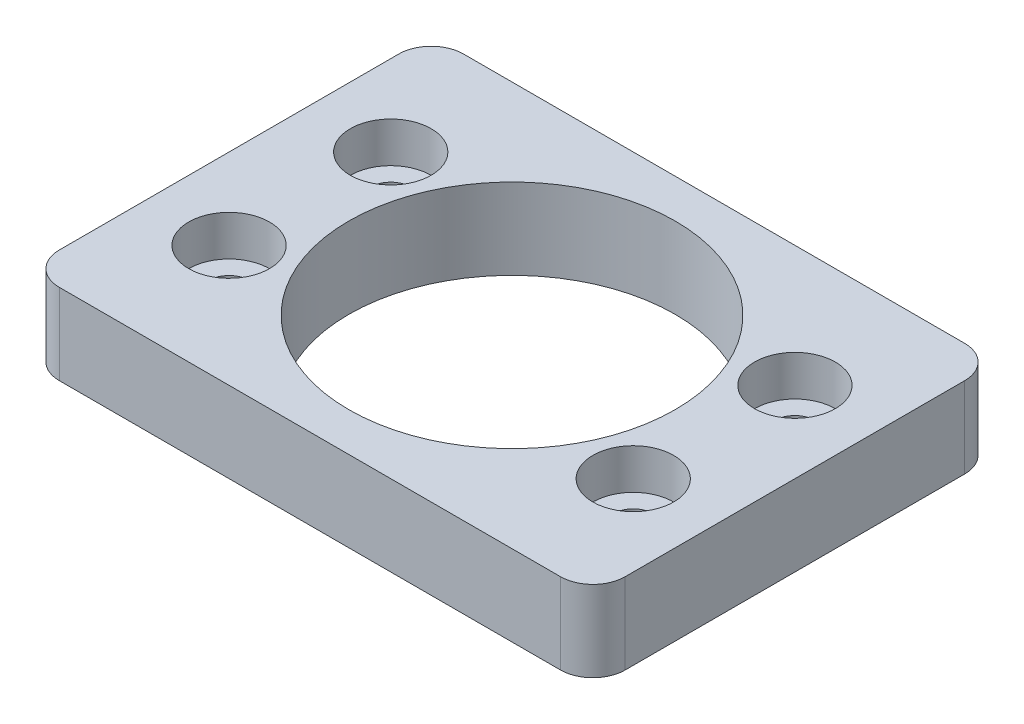
SolidWorks part; units mm, degrees
ref_plane "Front Plane" through (0, 0, 0) normal (0, 0, 1) x (1, 0, 0)
ref_plane "Top Plane" through (0, 0, 0) normal (0, 1, 0) x (1, 0, 0)
ref_plane "Right Plane" through (0, 0, 0) normal (1, 0, 0) x (0, 0, -1)
sketch "Sketch1" plane through (0, 0, 0) normal (0, 1, 0) x (1, 0, 0)
  line L0 (-31.75, 12.7) -> (31.75, 12.7) construction
  line L1 (-44.45, -31.75) -> (44.45, -31.75)
  line L2 (-44.45, -31.75) -> (-44.45, 31.75)
  line L3 (-44.45, 31.75) -> (44.45, 31.75)
  line L4 (44.45, -31.75) -> (44.45, 31.75)
  line L5 (-44.45, -31.75) -> (44.45, 31.75) construction
  line L6 (-44.45, 31.75) -> (44.45, -31.75) construction
  line L7 (31.75, 12.7) -> (31.75, -12.7) construction
  line L8 (31.75, -12.7) -> (-31.75, -12.7) construction
  line L9 (-31.75, -12.7) -> (-31.75, 12.7) construction
  line L10 (-31.75, 12.7) -> (31.75, -12.7) construction
  line L11 (31.75, 12.7) -> (-31.75, -12.7) construction
  circle A0 centre (0, 0) radius 25.654
  circle A1 centre (-31.75, 12.7) radius 3.175
  circle A2 centre (-31.75, -12.7) radius 3.175
  circle A3 centre (31.75, -12.7) radius 3.175
  circle A4 centre (31.75, 12.7) radius 3.175
  point P0 (0, 0)
  point P16 (0, 0)
  dimension "D1" = 51.308
  dimension "D6" = 6.35
  dimension "D2" = 63.5
  dimension "D3" = 25.4
  dimension "D4" = 63.5
  dimension "D5" = 88.9
extrude "Boss-Extrude1" add sketch "Sketch1" along normal blind 12.7
fillet "Fillet1" radius 5.08 4 edges at (-44.45, 6.35, -31.75) (44.45, 6.35, -31.75) (44.45, 6.35, 31.75) (-44.45, 6.35, 31.75)
sketch "Sketch2" plane through (0, 12.7, 0) normal (0, 1, 0) x (1, 0, 0)
  circle A0 centre (-31.75, 12.7) radius 6.35
  circle A1 centre (-31.75, -12.7) radius 6.35
  circle A2 centre (31.75, -12.7) radius 6.35
  circle A3 centre (31.75, 12.7) radius 6.35
  dimension "D1" = 12.7
extrude "Cut-Extrude1" cut sketch "Sketch2" against normal blind 6.35
